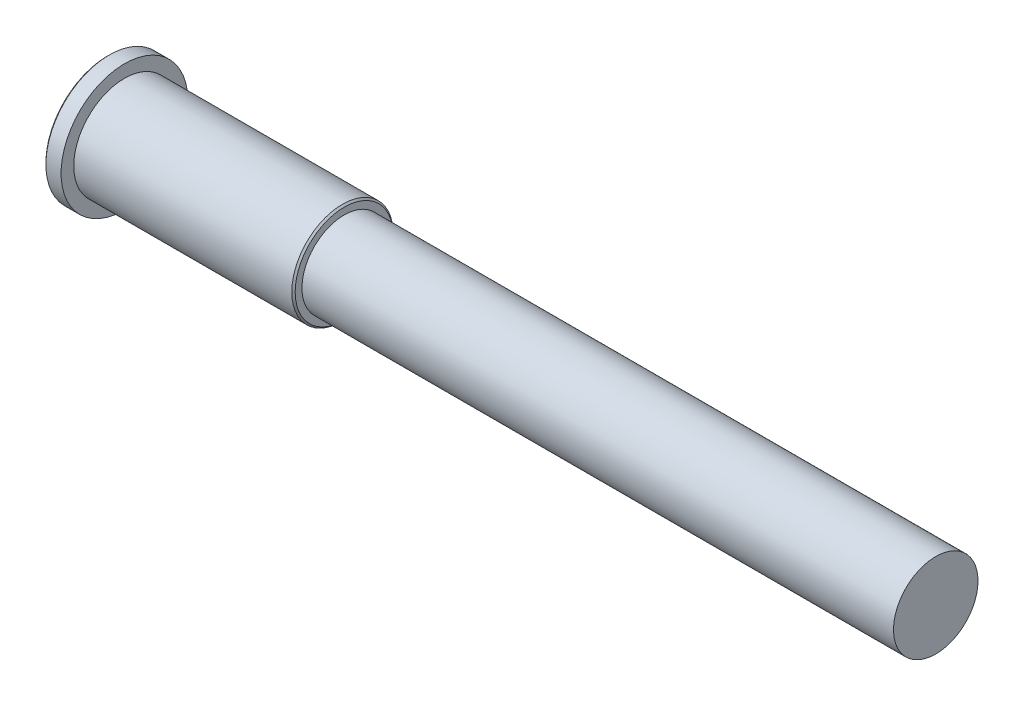
SolidWorks part; units mm, degrees
ref_plane "Front Plane" through (0, 0, 0) normal (0, 0, 1) x (1, 0, 0)
ref_plane "Top Plane" through (0, 0, 0) normal (0, 1, 0) x (1, 0, 0)
ref_plane "Right Plane" through (0, 0, 0) normal (1, 0, 0) x (0, 0, -1)
sketch "Sketch1" plane through (0, 0, 0) normal (1, 0, 0) x (0, 0, -1)
  circle A0 centre (0, 0) radius 7.5
  dimension "D1" = 15
extrude "Boss-Extrude1" add sketch "Sketch1" along normal blind 2
sketch "Sketch2" plane through (2, 0, 0) normal (1, 0, 0) x (0, 0, -1)
  circle A0 centre (0, 0) radius 6
  dimension "D1" = 12
extrude "Boss-Extrude2" add sketch "Sketch2" along normal blind 26
sketch "Sketch3" plane through (28, 0, 0) normal (1, 0, 0) x (0, 0, -1)
  circle A0 centre (0, 0) radius 5
  dimension "D1" = 10
extrude "Boss-Extrude3" add sketch "Sketch3" along normal blind 70
chamfer "Chamfer1" distance 0.2 angle 45 2 edges at (0, 0, -7.5) (28, 0, -6)
